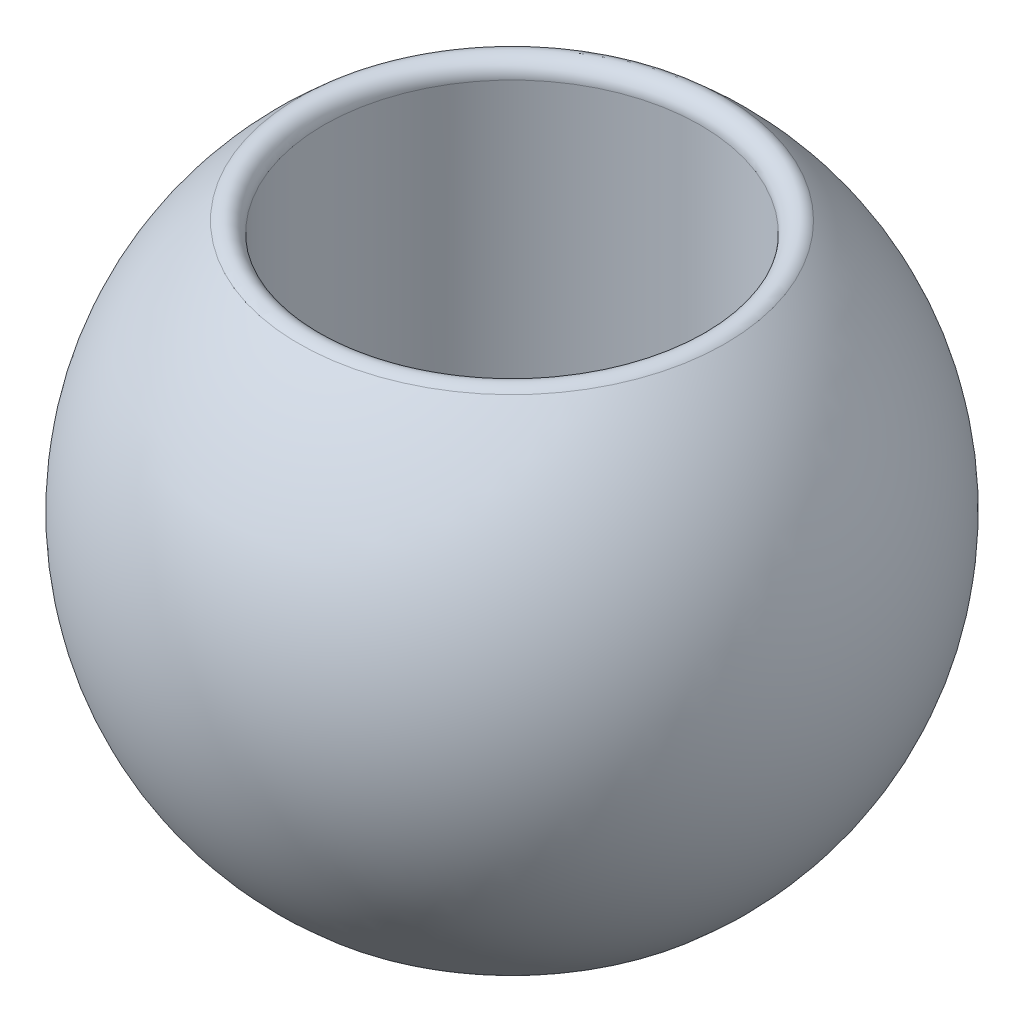
SolidWorks part; units mm, degrees
material "Chrome Stainless Steel"
ref_plane "Front Plane" through (0, 0, 0) normal (0, 0, 1) x (1, 0, 0)
ref_plane "Top Plane" through (0, 0, 0) normal (0, 1, 0) x (1, 0, 0)
ref_plane "Right Plane" through (0, 0, 0) normal (1, 0, 0) x (0, 0, -1)
sketch "Sketch1" plane through (0, 0, 0) normal (0, 0, 1) x (1, 0, 0)
  line L0 (0, 11.1125) -> (0, -11.1125)
  arc A0 (0, 11.1125) -> (0, -11.1125) centre (0, 0) ccw
revolve "Revolve1" add sketch "Sketch1" angle 360 about L0
sketch "Sketch2" plane through (0, 0, 0) normal (0, 1, 0) x (1, 0, 0)
  circle A0 centre (0, 0) radius 6.35
extrude "Cut-Extrude1" cut sketch "Sketch2" against normal mid plane 50.8
fillet "Fillet1" radius 0.508 2 edges at (0, 9.1195, -6.35) (0, -9.1195, 6.35)
